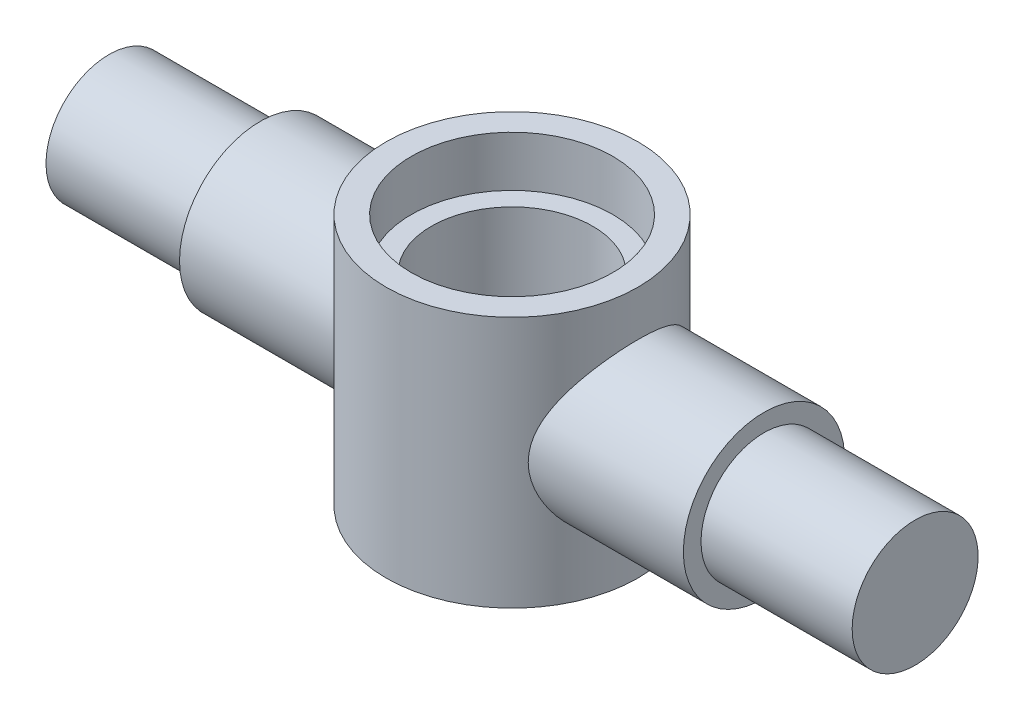
SolidWorks part; units mm, degrees
ref_plane "Front Plane" through (0, 0, 0) normal (0, 0, 1) x (1, 0, 0)
ref_plane "Top Plane" through (0, 0, 0) normal (0, 1, 0) x (1, 0, 0)
ref_plane "Right Plane" through (0, 0, 0) normal (1, 0, 0) x (0, 0, -1)
sketch "Sketch1" plane through (0, 0, 0) normal (0, 1, 0) x (1, 0, 0)
  circle A0 centre (0, 0) radius 25
  dimension "D1" = 50
extrude "Boss-Extrude1" add sketch "Sketch1" along normal mid plane 50
sketch "Sketch2" plane through (0, 0, 0) normal (0, 0, 1) x (1, 0, 0)
  line L1 (-50, 16) -> (50, 16)
  line L2 (50, 16) -> (50, 12.5)
  line L3 (50, 12.5) -> (80, 12.5)
  line L4 (80, 12.5) -> (80, 0)
  line L6 (80, 0) -> (0, 0) construction
  line L7 (0, 0) -> (0, 16) construction
  line L8 (-80, 12.5) -> (-80, 0)
  line L9 (-50, 12.5) -> (-80, 12.5)
  line L10 (-50, 16) -> (-50, 12.5)
  line L11 (-80, 0) -> (80, 0)
  dimension "D1" = 25
  dimension "D2" = 32
  dimension "D3" = 50
  dimension "D4" = 80
revolve "Revolve1" add sketch "Sketch2" angle 360 about L11
sketch "Sketch6" plane through (0, 25, 0) normal (0, 1, 0) x (1, 0, 0)
  point P0 (0, 0)
hole_wizard "CBORE for M16 Hex Head Bolt1" positions "Sketch6" profile "Sketch4" counterbore size "M16" standard "DIN"
sketch "Sketch4" plane through (0, 25, 0) normal (1, 0, 0) x (0, 0, 1)
  line L0 (0, 0) -> (0, 59.6138)
  line L1 (0, 59.6138) -> (16, 50)
  line L2 (16, 50) -> (16, 10)
  line L3 (16, 10) -> (20, 10)
  line L4 (20, 10) -> (20, 0)
  line L5 (20, 0) -> (0, 0)
  line L10 (0, 59.6138) -> (-16, 50) construction
  line L11 (0, -6.35) -> (0, 107.95) construction
  dimension "Hole Dia." = 32
  dimension "Hole Depth" = 50
  dimension "C'Bore Dia." = 40
  dimension "C'Bore Depth" = 10
  dimension "Drill Angle" = 118
